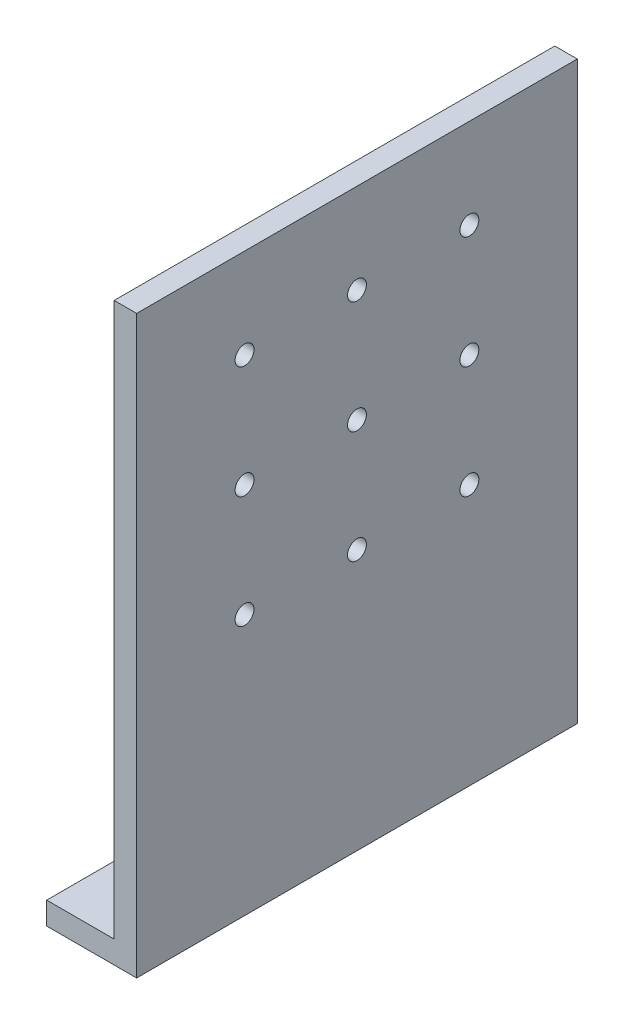
SolidWorks part; units mm, degrees
material "1.4511 (X3CrNb17)"
ref_plane "前视基准面" through (0, 0, 0) normal (0, 0, 1) x (1, 0, 0)
ref_plane "上视基准面" through (0, 0, 0) normal (0, 1, 0) x (1, 0, 0)
ref_plane "右视基准面" through (0, 0, 0) normal (1, 0, 0) x (0, 0, -1)
sketch "草图1" plane through (0, 0, 0) normal (0, 0, 1) x (1, 0, 0)
  line L0 (0, 0) -> (0, 128)
  line L1 (0, 128) -> (-5, 128)
  line L2 (-5, 128) -> (-5, 5)
  line L3 (-5, 5) -> (-20, 5)
  line L4 (-20, 5) -> (-20, 0)
  line L5 (-20, 0) -> (0, 0)
  dimension "D1" = 128
  dimension "D2" = 5
  dimension "D3" = 123
  dimension "D4" = 15
extrude "凸台-拉伸1" add sketch "草图1" along normal blind 98
sketch "草图2" plane through (0, 5, 0) normal (0, 1, 0) x (1, 0, 0)
  line L0 (-12.5, -24) -> (-12.5, -74) construction
  line L1 (-5, -98) -> (-20, -98) construction
  line L2 (-20, -98) -> (-20, 0) construction
  point P2 (-12.5, -49)
  dimension "D1" = 50
  dimension "D2" = 49
  dimension "D3" = 7.5
hole_wizard "M5 螺纹孔1" positions "草图3" profile "草图4" tap size "M5" standard "GB"
sketch "草图3" plane through (0, 5, 0) normal (0, 1, 0) x (1, 0, 0)
  point P0 (-12.5, -24)
  point P3 (-12.5, -74)
sketch "草图4" plane through (-12.5, 5, 24) normal (1, 0, 0) x (0, 0, 1)
  line L0 (0, 0) -> (0, 15.2618)
  line L1 (0, 15.2618) -> (2.1, 14)
  line L2 (2.1, 14) -> (2.1, 0)
  line L5 (2.1, 0) -> (0, 0)
  line L10 (0, 15.2618) -> (-2.1, 14) construction
  line L11 (0, -6.35) -> (0, 107.95) construction
  dimension "螺纹孔钻头直径" = 4.2
  dimension "螺纹孔钻头深度" = 14
  dimension "导头角度" = 118
cosmetic thread "孔螺蚊线1" parameters "D1"=10, "D2"=5
cosmetic thread "孔螺蚊线2" parameters "D1"=10, "D2"=5
sketch "草图5" plane through (-5, 0, 0) normal (-1, 0, 0) x (0, 0, 1)
  line L0 (98, 128) -> (98, 5) construction
  line L1 (24, 108) -> (74, 108) construction
  line L2 (24, 108) -> (24, 58) construction
  line L3 (24, 58) -> (74, 58) construction
  line L4 (74, 108) -> (74, 58) construction
  line L5 (24, 108) -> (74, 58) construction
  line L6 (24, 58) -> (74, 108) construction
  line L7 (98, 128) -> (0, 128) construction
  line L8 (24, 83) -> (74, 83) construction
  line L9 (49, 108) -> (49, 58) construction
  point P0 (49, 83)
  dimension "D1" = 50
  dimension "D2" = 50
  dimension "D3" = 24
  dimension "D4" = 20
hole_wizard "M5 螺纹孔2" positions "草图8" profile "草图9" tap size "M5" standard "GB"
sketch "草图8" plane through (-5, 0, 0) normal (-1, 0, 0) x (0, 0, 1)
  line L0 (74, 108) -> (74, 58) construction
  line L1 (24, 108) -> (74, 108) construction
  line L2 (24, 58) -> (74, 108) construction
  point P0 (24, 58)
  point P3 (49, 58)
  point P6 (74, 58)
  point P9 (74, 83)
  point P13 (74, 108)
  point P16 (49, 108)
  point P20 (24, 108)
  point P23 (24, 83)
  point P26 (49, 83)
sketch "草图9" plane through (-5, 58, 24) normal (0, 1, 0) x (0, 0, 1)
  line L0 (0, 0) -> (0, 15.2618)
  line L1 (0, 15.2618) -> (2.1, 14)
  line L2 (2.1, 14) -> (2.1, 0)
  line L5 (2.1, 0) -> (0, 0)
  line L10 (0, 15.2618) -> (-2.1, 14) construction
  line L11 (0, -6.35) -> (0, 107.95) construction
  dimension "螺纹孔钻头直径" = 4.2
  dimension "螺纹孔钻头深度" = 14
  dimension "导头角度" = 118
cosmetic thread "孔螺蚊线3" parameters "D1"=10, "D2"=5
cosmetic thread "孔螺蚊线4" parameters "D1"=10, "D2"=5
cosmetic thread "孔螺蚊线5" parameters "D1"=10, "D2"=5
cosmetic thread "孔螺蚊线6" parameters "D1"=10, "D2"=5
cosmetic thread "孔螺蚊线7" parameters "D1"=10, "D2"=5
cosmetic thread "孔螺蚊线8" parameters "D1"=10, "D2"=5
cosmetic thread "孔螺蚊线9" parameters "D1"=10, "D2"=5
cosmetic thread "孔螺蚊线10" parameters "D1"=10, "D2"=5
cosmetic thread "孔螺蚊线11" parameters "D1"=10, "D2"=5
